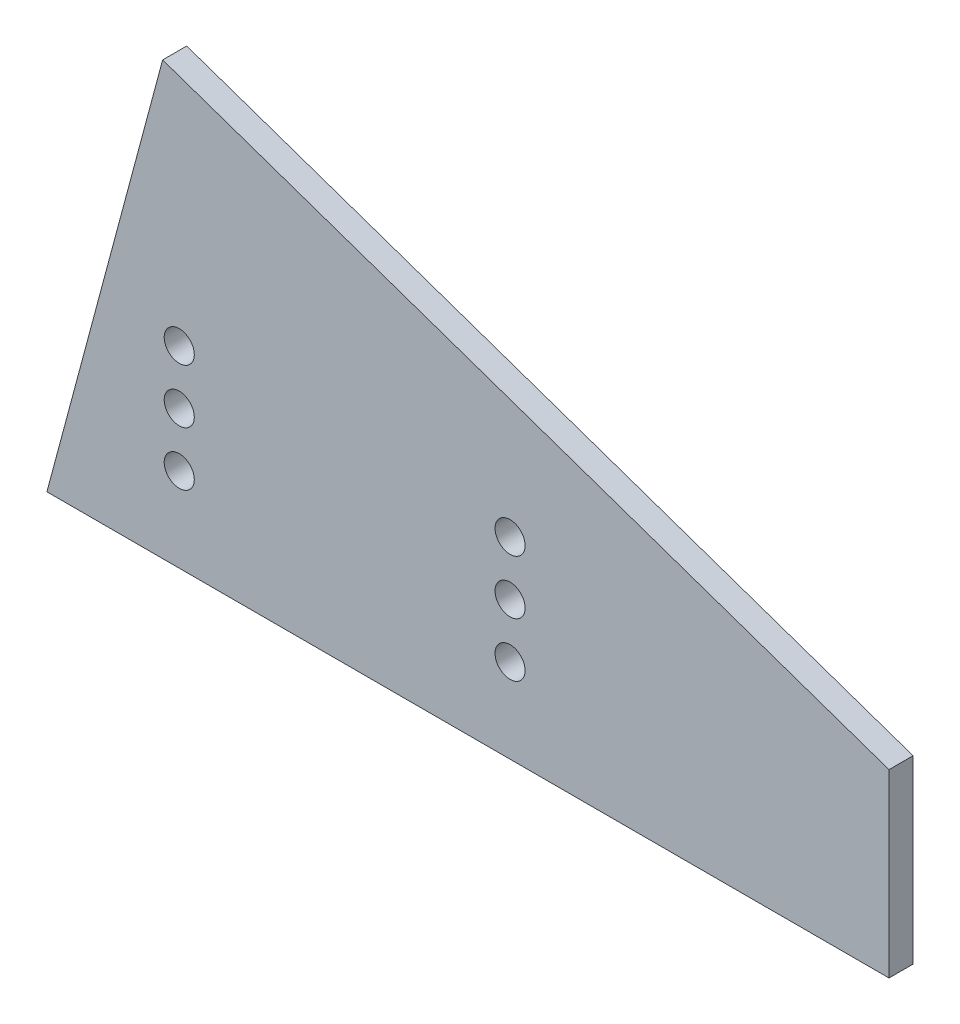
SolidWorks part; units mm, degrees
ref_plane "Front Plane" through (0, 0, 0) normal (0, 0, 1) x (1, 0, 0)
ref_plane "Top Plane" through (0, 0, 0) normal (0, 1, 0) x (1, 0, 0)
ref_plane "Right Plane" through (0, 0, 0) normal (1, 0, 0) x (0, 0, -1)
sketch "Sketch1" plane through (0, 0, 0) normal (0, 0, 1) x (1, 0, 0)
  line L4 (75.4217, -40) -> (75.4217, -10)
  line L5 (-64.5783, -40) -> (75.4217, -40)
  line L9 (75.4217, -10) -> (-45.3378, 31.8066)
  line L10 (-64.5783, -40) -> (-45.3378, 31.8066)
  point P0 (0, 0)
  dimension "D1" = 140
  dimension "D2" = 30
  dimension "D3" = 40
extrude "Boss-Extrude1" add sketch "Sketch1" along normal blind 4
sketch "Sketch2" plane through (0, 0, 4) normal (0, 0, 1) x (1, 0, 0)
  line L0 (-64.5783, -40) -> (75.4217, -40) construction
  circle A1 centre (-42.5783, -17) radius 2.5
  circle A2 centre (-42.5783, -8) radius 2.5
  circle A3 centre (-42.5783, -26) radius 2.5
  circle A4 centre (12.4217, -17) radius 2.5
  circle A5 centre (12.4217, -8) radius 2.5
  circle A6 centre (12.4217, -26) radius 2.5
  dimension "D1" = 5
  dimension "D2" = 5
  dimension "D6" = 5
  dimension "D7" = 5
  dimension "D8" = 5
  dimension "D10" = 5
  dimension "D3" = 23
  dimension "D4" = 9
  dimension "D5" = 9
  dimension "D9" = 9
  dimension "D11" = 9
  dimension "D12" = 23
  dimension "D13" = 55
  dimension "D14" = 22
extrude "Cut-Extrude1" cut sketch "Sketch2" against normal blind 10
